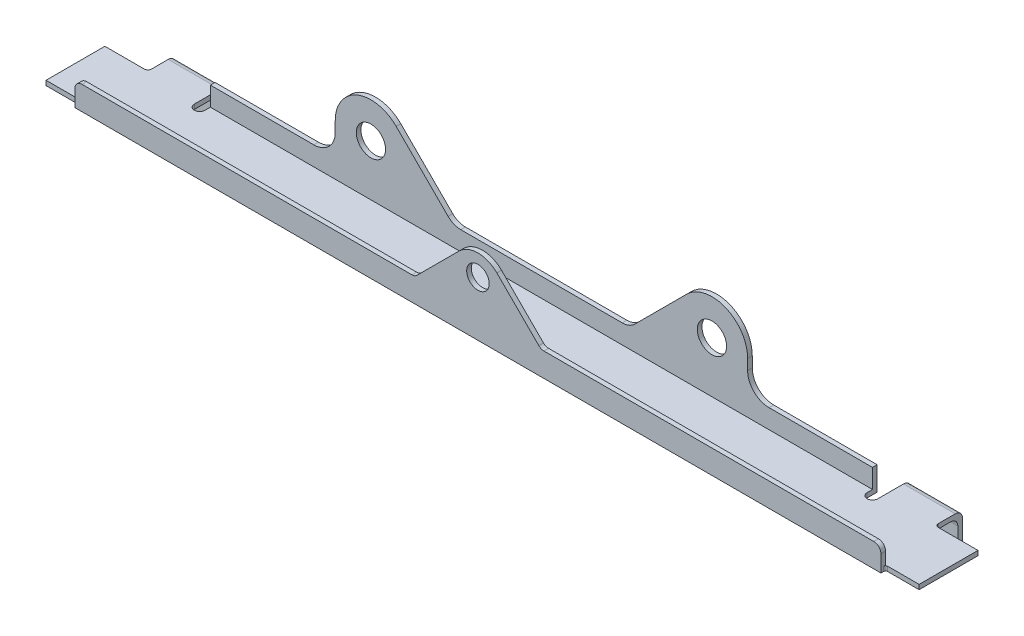
SolidWorks part; units mm, degrees
ref_plane "Front Plane" through (0, 0, 0) normal (0, 0, 1) x (1, 0, 0)
ref_plane "Top Plane" through (0, 0, 0) normal (0, 1, 0) x (1, 0, 0)
ref_plane "Right Plane" through (0, 0, 0) normal (1, 0, 0) x (0, 0, -1)
sketch "Sketch1" plane through (0, 0, 0) normal (0, 1, 0) x (1, 0, 0)
  line L0 (117.8369, 12.1285) -> (117.1861, 12.1285)
  line L1 (-143.4401, -12.1285) -> (143.4401, -12.1285)
  line L4 (155.3782, -10.4775) -> (155.3782, 10.4775)
  line L5 (155.3782, -10.4775) -> (155.3782, 10.4775)
  line L6 (155.3782, -10.4775) -> (144.2021, -10.4775)
  line L7 (143.4401, -11.2395) -> (143.4401, -12.1285)
  line L8 (140.0619, 12.1285) -> (140.0619, 20.2565)
  line L9 (155.3782, 10.4775) -> (143.4401, 10.4775)
  line L10 (143.4401, 10.4775) -> (141.332, 10.4775)
  line L11 (140.0619, 11.7475) -> (140.0619, 12.1285)
  line L16 (140.0619, 20.2565) -> (121.6469, 20.2565)
  line L17 (121.6469, 20.2565) -> (121.6469, 12.1285)
  line L18 (0, 0) -> (0, 40.6326) construction
  line L19 (117.8369, 8.5725) -> (117.8369, 12.1285)
  line L20 (-121.6469, 20.2565) -> (-121.6469, 12.1285)
  line L21 (-140.0619, 20.2565) -> (-121.6469, 20.2565)
  line L22 (-140.0619, 11.7475) -> (-140.0619, 12.1285)
  line L23 (-143.4401, 10.4775) -> (-141.332, 10.4775)
  line L24 (-155.3782, 10.4775) -> (-143.4401, 10.4775)
  line L25 (-140.0619, 12.1285) -> (-140.0619, 20.2565)
  line L26 (-143.4401, -11.2395) -> (-143.4401, -12.1285)
  line L27 (-155.3782, -10.4775) -> (-144.2021, -10.4775)
  line L28 (-155.3782, -10.4775) -> (-155.3782, 10.4775)
  line L29 (-155.3782, -10.4775) -> (-155.3782, 10.4775)
  line L30 (-117.1861, 12.1285) -> (117.1861, 12.1285)
  line L31 (-121.6469, 12.1285) -> (-121.6469, 8.5725)
  line L32 (-117.8369, 8.5725) -> (-117.8369, 12.1285)
  line L33 (-117.8369, 12.1285) -> (-117.1861, 12.1285)
  line L34 (121.6469, 12.1285) -> (121.6469, 8.5725)
  arc A1 (141.332, 10.4775) -> (140.0619, 11.7475) centre (141.3319, 11.7475) cw
  arc A2 (121.6469, 8.5725) -> (117.8369, 8.5725) centre (119.7419, 8.5725) cw
  arc A3 (143.4401, -11.2395) -> (144.2021, -10.4775) centre (144.2021, -11.2395) cw
  arc A4 (-143.4401, -11.2395) -> (-144.2021, -10.4775) centre (-144.2021, -11.2395) ccw
  arc A5 (-121.6469, 8.5725) -> (-117.8369, 8.5725) centre (-119.7419, 8.5725) ccw
  arc A6 (-141.332, 10.4775) -> (-140.0619, 11.7475) centre (-141.3319, 11.7475) ccw
  point P0 (0, 0)
  point P9 (155.3782, 1.0363)
  point P12 (155.3782, 0)
  point P22 (140.0619, 10.4775)
  point P27 (143.4401, -10.4775)
  point P50 (-143.4401, -10.4775)
  point P51 (-140.0619, 10.4775)
  point P52 (-155.3782, 0)
  point P53 (-155.3782, 1.0363)
  dimension "D7" = 1.27
  dimension "D9" = 0.762
  dimension "D11" = 3.81
  dimension "D1" = 3.3782
  dimension "D3" = 18.415
  dimension "D4" = 11.938
  dimension "D5" = 8.128
extrude "Boss-Extrude1" add sketch "Sketch1" along normal blind 1.651
sketch "Sketch2" plane through (0, 0, 0) normal (0, -1, 0) x (1, 0, 0)
  line L0 (-121.6469, -20.2565) -> (-121.6469, -8.5725) construction
  line L1 (-140.0619, -20.2565) -> (-121.6469, -20.2565)
  line L2 (-140.0619, -20.2565) -> (-140.0619, -18.6055)
  line L3 (-140.0619, -18.6055) -> (-121.6469, -18.6055)
  line L4 (-121.6469, -20.2565) -> (-121.6469, -18.6055)
  line L5 (0, 0) -> (0, -3.8993) construction
  line L6 (121.6469, -20.2565) -> (121.6469, -18.6055)
  line L7 (140.0619, -18.6055) -> (121.6469, -18.6055)
  line L8 (140.0619, -20.2565) -> (140.0619, -18.6055)
  line L9 (140.0619, -20.2565) -> (121.6469, -20.2565)
  dimension "D1" = 1.651
extrude "Boss-Extrude2" add sketch "Sketch2" along normal blind 10.287
fillet "Fillet1" radius 2.54 4 edges at (130.8544, 1.651, -20.2565) (-130.8544, 1.651, -20.2565) (130.8544, 0, -18.6055) (-130.8544, 0, -18.6055)
fillet "Fillet3" radius 1.27 4 edges at (121.6469, -10.287, -19.431) (140.0619, -10.287, -19.431) (-140.0619, -10.287, -19.431) (-121.6469, -10.287, -19.431)
sketch "Sketch4" plane through (0, 1.651, 0) normal (0, 1, 0) x (1, 0, 0)
  line L0 (-117.8369, 12.1285) -> (-117.8369, 10.4775)
  line L1 (-117.8369, 8.5725) -> (-117.8369, 12.1285) construction
  line L2 (117.8369, 12.1285) -> (117.8369, 10.4775)
  line L3 (117.8369, 8.5725) -> (117.8369, 12.1285) construction
  line L4 (117.8369, 10.4775) -> (-117.8369, 10.4775)
  line L5 (-117.8369, 12.1285) -> (117.8369, 12.1285)
  line L7 (-143.4401, -12.1285) -> (143.4401, -12.1285)
  line L8 (-143.4401, -12.1285) -> (-143.4401, -10.4775)
  line L9 (-143.4401, -10.4775) -> (143.4401, -10.4775)
  line L10 (143.4401, -12.1285) -> (143.4401, -10.4775)
  dimension "D1" = 1.651
  dimension "D2" = 1.651
  dimension "D3" = 1.651
extrude "Boss-Extrude3" add sketch "Sketch4" along normal blind 30.861
sketch "Sketch5" plane through (0, 0, 12.1285) normal (0, 0, 1) x (1, 0, 0)
  line L0 (-143.4401, 1.651) -> (143.4401, 1.651)
  line L1 (143.4401, 1.651) -> (143.4401, 8.4582)
  line L2 (143.4401, 32.512) -> (143.4401, 0) construction
  line L3 (143.4401, 8.4582) -> (22.4345, 8.4582)
  line L4 (0, 19.431) -> (0, 12.2555)
  line L6 (-143.4401, 8.4582) -> (-22.4345, 8.4582)
  line L10 (-143.4401, 8.4582) -> (-143.4401, 32.512)
  line L11 (-143.4401, 32.512) -> (143.4401, 32.512)
  line L12 (143.4401, 32.512) -> (143.4401, 8.4582)
  line L13 (-22.4345, 8.4582) -> (-6.7352, 24.1576)
  line L14 (22.4345, 8.4582) -> (6.7352, 24.1576)
  arc A1 (6.7352, 24.1576) -> (-6.7352, 24.1576) centre (0, 17.4224) ccw
  circle A2 centre (0, 19.431) radius 4.0005
  point P17 (0, 19.431)
  dimension "D5" = 8.001
  dimension "D4" = 9.525
  dimension "D1" = 6.8072
  dimension "D2" = 121.0056
  dimension "D3" = 7.1755
extrude "Cut-Extrude2" cut sketch "Sketch5" against normal blind 2.54
sketch "Sketch11" plane through (0, 0, -12.1285) normal (0, 0, -1) x (-1, 0, 0)
  line L0 (117.8369, 1.651) -> (-117.8369, 1.651)
  line L1 (-117.8369, 32.512) -> (-117.8369, 0) construction
  line L2 (-117.8369, 1.651) -> (-121.6469, 1.651) construction
  line L3 (-117.8369, 1.651) -> (-117.8369, 8.4582)
  line L4 (-143.4401, 8.4582) -> (-22.4345, 8.4582) construction
  line L6 (143.4401, 8.4582) -> (22.4345, 8.4582) construction
  line L7 (117.8369, 32.512) -> (117.8369, 0) construction
  line L8 (117.8369, 8.4582) -> (117.8369, 1.651)
  line L10 (-73.3869, 16.0782) -> (-73.3869, 19.812)
  line L11 (-117.8369, 32.512) -> (117.8369, 32.512) construction
  line L13 (-60.6869, 32.512) -> (-60.6869, 19.812)
  line L14 (0, 0) -> (0, 13.4778)
  line L17 (-81.007, 8.4582) -> (-117.8369, 8.4582)
  line L20 (60.6869, 32.512) -> (60.6869, 19.812)
  line L21 (73.3869, 19.812) -> (73.3869, 16.0782)
  line L22 (81.007, 8.4582) -> (117.8369, 8.4582)
  line L24 (-60.6869, 32.512) -> (60.6869, 32.512)
  line L25 (117.8369, 8.4582) -> (117.8369, 32.512)
  line L26 (117.8369, 32.512) -> (60.6869, 32.512)
  line L27 (-117.8369, 8.4582) -> (-117.8369, 32.512)
  line L28 (-117.8369, 32.512) -> (-60.6869, 32.512)
  line L29 (-51.7067, 28.7923) -> (-33.2325, 10.3181)
  line L30 (0, 8.4582) -> (-31.3726, 8.4582)
  line L31 (51.7067, 28.7923) -> (33.2325, 10.3181)
  line L32 (-28.7424, 8.4582) -> (28.7424, 8.4582)
  arc A0 (-51.7067, 28.7923) -> (-73.3869, 19.812) centre (-60.6869, 19.812) ccw
  circle A1 centre (-60.6869, 19.812) radius 5.207
  arc A6 (-81.007, 8.4582) -> (-73.3869, 16.0782) centre (-81.0069, 16.0782) ccw
  arc A7 (81.007, 8.4582) -> (73.3869, 16.0782) centre (81.0069, 16.0782) cw
  circle A12 centre (60.6869, 19.812) radius 5.207
  arc A13 (51.7067, 28.7923) -> (73.3869, 19.812) centre (60.6869, 19.812) cw
  arc A14 (28.7424, 8.4582) -> (33.2325, 10.3181) centre (28.7424, 14.8082) ccw
  arc A15 (-33.2325, 10.3181) -> (-28.7424, 8.4582) centre (-28.7424, 14.8082) ccw
  point P32 (-22.5869, 8.4582)
  point P37 (-22.5869, 18.8722)
  point P40 (-73.3869, 8.4582)
  point P63 (73.3869, 8.4582)
  point P64 (22.5869, 18.8722)
  point P65 (22.5869, 8.4582)
  dimension "D7" = 10.414
  dimension "D10" = 7.62
  dimension "D2" = 6.35
  dimension "D1" = 44.45
  dimension "D3" = 12.7
  dimension "D4" = 95.25
  dimension "D5" = 10.414
fillet "Fillet4" radius 2.54 4 edges at (143.4401, 8.4582, 11.303) (22.4345, 8.4582, 11.303) (-22.4345, 8.4582, 11.303) (-143.4401, 8.4582, 11.303)
extrude "Cut-Extrude3" cut sketch "Sketch11" against normal blind 7.62
